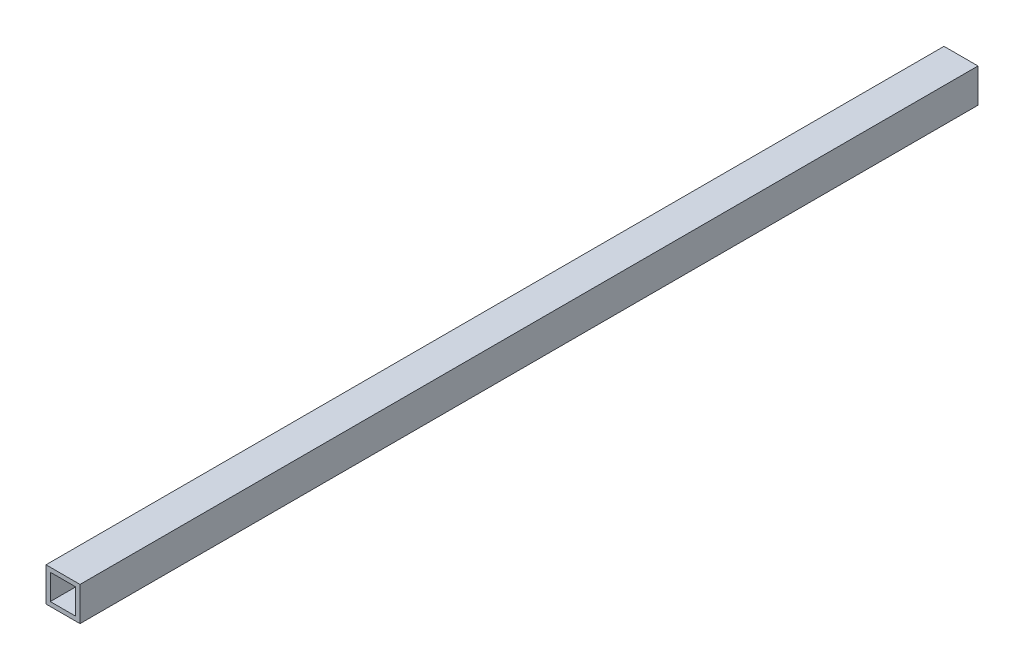
SolidWorks part; units mm, degrees
ref_plane "Front Plane" through (0, 0, 0) normal (0, 0, 1) x (1, 0, 0)
ref_plane "Top Plane" through (0, 0, 0) normal (0, 1, 0) x (1, 0, 0)
ref_plane "Right Plane" through (0, 0, 0) normal (1, 0, 0) x (0, 0, -1)
sketch "Sketch1" plane through (0, 0, 0) normal (0, 0, 1) x (1, 0, 0)
  line L1 (-6.06, 6.06) -> (6.06, 6.06)
  line L2 (-6.06, 6.06) -> (-6.06, -6.06)
  line L3 (-6.06, -6.06) -> (6.06, -6.06)
  line L4 (6.06, 6.06) -> (6.06, -6.06)
  line L5 (-6.06, 6.06) -> (6.06, -6.06) construction
  line L6 (-6.06, -6.06) -> (6.06, 6.06) construction
  line L7 (-4.53, 4.53) -> (4.53, 4.53)
  line L8 (-4.53, 4.53) -> (-4.53, -4.53)
  line L9 (-4.53, -4.53) -> (4.53, -4.53)
  line L10 (4.53, 4.53) -> (4.53, -4.53)
  line L11 (-4.53, 4.53) -> (4.53, -4.53) construction
  line L12 (-4.53, -4.53) -> (4.53, 4.53) construction
  point P0 (0, 0)
  point P6 (0, 0)
  dimension "D1" = 1.53
  dimension "D2" = 12.12
extrude "Boss-Extrude1" add sketch "Sketch1" along normal mid plane 320
